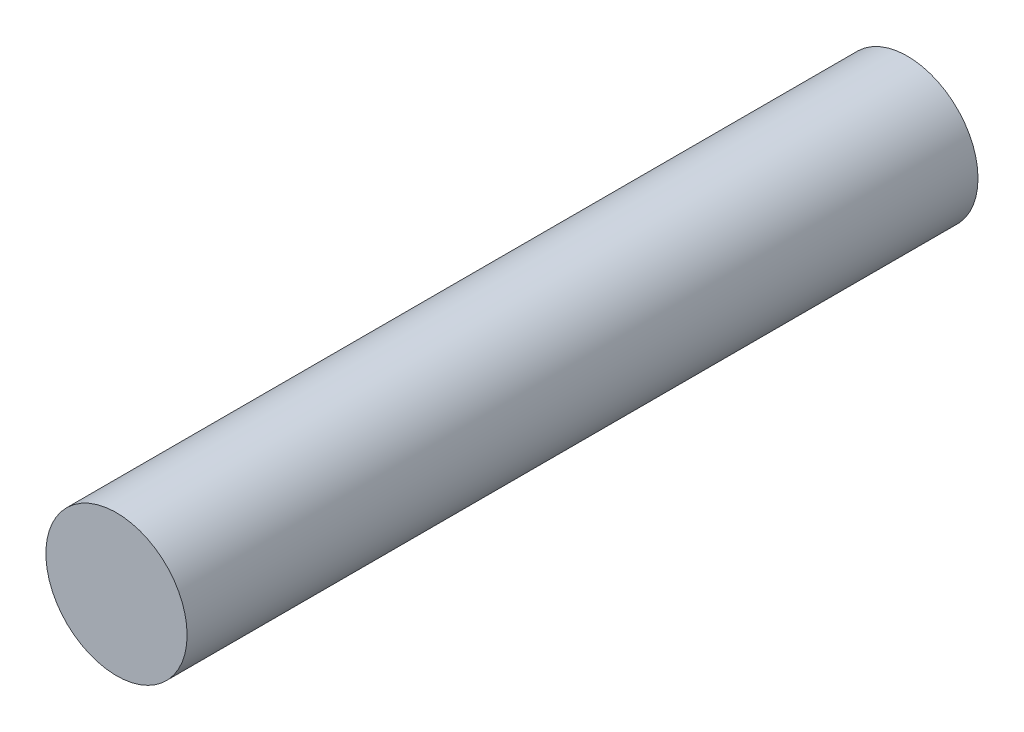
SolidWorks part; units mm, degrees
ref_plane "前视基准面" through (0, 0, 0) normal (0, 0, 1) x (1, 0, 0)
ref_plane "上视基准面" through (0, 0, 0) normal (0, 1, 0) x (1, 0, 0)
ref_plane "右视基准面" through (0, 0, 0) normal (1, 0, 0) x (0, 0, -1)
other "Configuration Table"
sketch "草图1" plane through (0, 0, 0) normal (0, 0, 1) x (1, 0, 0)
  circle A0 centre (0, 0) radius 2.5
  dimension "diameter" = 5
extrude "Double_ear_pin" add sketch "草图1" along normal blind 28
